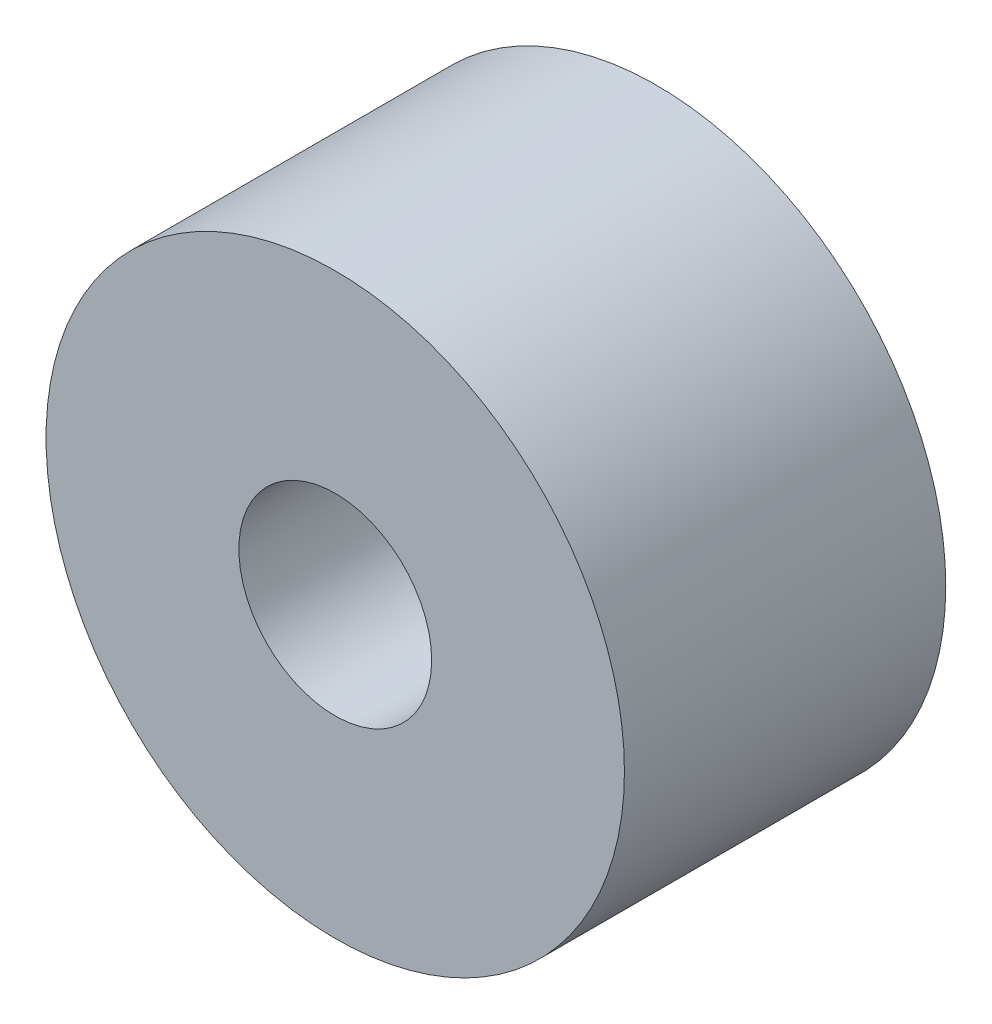
SolidWorks part; units mm, degrees
ref_plane "Front Plane" through (0, 0, 0) normal (0, 0, 1) x (1, 0, 0)
ref_plane "Top Plane" through (0, 0, 0) normal (0, 1, 0) x (1, 0, 0)
ref_plane "Right Plane" through (0, 0, 0) normal (1, 0, 0) x (0, 0, -1)
sketch "Sketch1" plane through (0, 0, 0) normal (0, 0, 1) x (1, 0, 0)
  circle A0 centre (0, 0) radius 4.5
  circle A1 centre (0, 0) radius 1.5
  dimension "D1" = 9
  dimension "D2" = 3
extrude "Boss-Extrude1" add sketch "Sketch1" along normal blind 5
